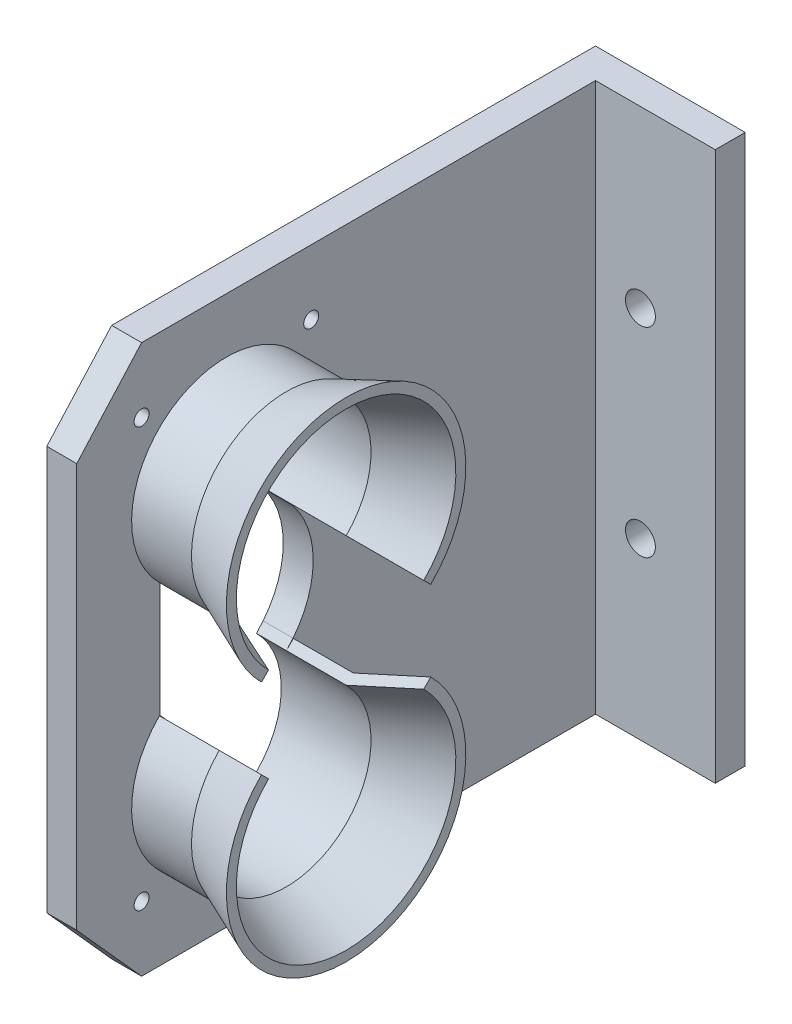
SolidWorks part; units mm, degrees
ref_plane "前视基准面" through (0, 0, 0) normal (0, 0, 1) x (1, 0, 0)
ref_plane "上视基准面" through (0, 0, 0) normal (0, 1, 0) x (1, 0, 0)
ref_plane "右视基准面" through (0, 0, 0) normal (1, 0, 0) x (0, 0, -1)
other "Configuration Table"
sketch "草图1" plane through (0, 0, 0) normal (0, 1, 0) x (1, 0, 0)
  line L7 (22.8824, -27.7157) -> (25.8824, -27.7157)
  line L8 (25.8824, -27.7157) -> (25.8824, 24.2843)
  line L9 (25.8824, 24.2843) -> (37.8824, 24.2843)
  line L10 (37.8824, 24.2843) -> (37.8824, 27.2843)
  line L11 (37.8824, 27.2843) -> (22.8824, 27.2843)
  line L12 (22.8824, 27.2843) -> (22.8824, -27.7157)
extrude "凸台-拉伸1" add sketch "草图1" along normal mid plane 55
ref_plane "基准面1" through (0, 0, -27.2843) normal (0, 0, -1) x (-1, 0, 0)
sketch "草图2" plane through (0, 0, -27.2843) normal (0, 0, -1) x (-1, 0, 0)
  line L3 (-25.8824, 27.5) -> (-25.8824, -27.5)
  line L4 (-24.3824, 27.5) -> (-24.3824, -27.5)
  line L5 (-25.8824, 27.5) -> (-10.8824, 27.5) construction
  line L6 (-25.8824, -27.5) -> (-10.8824, -27.5) construction
  line L7 (-22.8824, 27.5) -> (-22.8824, -27.5)
  circle A2 centre (-30.3824, -10) radius 1.5
  circle A3 centre (-30.3824, 10) radius 1.5
  dimension "D4" = 1.5
ref_plane "基准面2" through (25.8824, 0, 0) normal (1, 0, 0) x (0, 0, -1)
sketch "草图3" plane through (25.8824, 0, 0) normal (1, 0, 0) x (0, 0, -1)
  line L0 (-27.7157, 27.5) -> (-27.7157, -27.5) construction
  line L1 (-22.7157, 22.5) -> (-2.7157, 22.5)
  line L2 (-22.7157, 22.5) -> (-22.7157, -22.5)
  line L3 (-22.7157, -22.5) -> (-2.7157, -22.5)
  line L4 (-2.7157, 22.5) -> (-2.7157, -22.5)
  line L5 (-22.7157, 22.5) -> (-2.7157, -22.5) construction
  line L6 (-22.7157, -22.5) -> (-2.7157, 22.5) construction
  line L7 (-12.7157, 22.5) -> (-12.7157, 22)
  line L8 (-12.7157, 12.5) -> (-6.7053, 6.4896)
  line L9 (-12.7157, 12.5) -> (-18.7261, 6.4896)
  line L10 (-12.7157, -12.5) -> (-18.7261, -6.4896)
  line L11 (-12.7157, -12.5) -> (-6.7053, -6.4896)
  line L12 (-12.7157, -22) -> (-12.7157, -22.5)
  line L13 (-12.7157, -4) -> (-12.7157, -21)
  line L14 (-12.7157, 3) -> (-12.7157, -3)
  line L15 (-12.7157, 21) -> (-12.7157, 4)
  line L16 (-22.7157, 0) -> (-2.7157, 0)
  line L17 (-18.7261, 6.4896) -> (-19.3945, 5.744)
  line L18 (-6.7053, 6.4896) -> (-6.0369, 5.744)
  line L19 (-6.0369, -5.744) -> (-6.7053, -6.4896)
  line L20 (-19.3945, -5.744) -> (-18.7261, -6.4896)
  line L21 (-19.3945, 5.744) -> (-19.3945, -5.744)
  line L22 (-27.7157, 27.5) -> (-27.7157, 20.2498)
  line L23 (-27.7157, 20.2498) -> (-21.2157, 27.5)
  line L24 (-27.7157, 27.5) -> (27.2843, 27.5) construction
  line L25 (-21.2157, 27.5) -> (-27.7157, 27.5)
  line L26 (-27.7157, -20.2498) -> (-21.2157, -27.5)
  line L27 (-27.7157, -27.5) -> (-27.7157, -20.2498)
  line L28 (-21.2157, -27.5) -> (-27.7157, -27.5)
  circle A0 centre (-12.7157, 12.5) radius 8.5
  circle A1 centre (-12.7157, -12.5) radius 8.5
  arc A2 (-6.0369, 5.744) -> (-6.0369, -5.744) centre (-13.1949, 0) cw
  circle A4 centre (-12.7157, 12.5) radius 9.5
  circle A5 centre (-12.7157, -12.5) radius 9.5
  circle A6 centre (-4.2157, -21) radius 0.75
  circle A7 centre (-21.2157, -21) radius 0.75
  circle A8 centre (-4.2157, 21) radius 0.75
  circle A9 centre (-21.2157, 21) radius 0.75
  point P0 (0, 0)
  dimension "D6" = 17
  dimension "D7" = 17
  dimension "D8" = 19
  dimension "D9" = 19
  dimension "D11" = 1.5
  dimension "D1" = 45
  dimension "D2" = 20
  dimension "D3" = 5
  dimension "D4" = 10
  dimension "D5" = 10
  dimension "D10" = 1.5
  dimension "D12" = 1.5
  dimension "D13" = 6.5
extrude "切除-拉伸3" cut sketch "草图3" against normal blind 3
ref_plane "基准面4" through (0, 0, 12.7157) normal (0, 0, 1) x (0, -1, 0)
sketch "草图5" plane through (0, 0, 12.7157) normal (0, 0, 1) x (0, -1, 0)
  line L0 (-3, 25.8824) -> (-22, 25.8824) construction
  line L2 (-3, 25.8824) -> (-22, 25.8824)
  line L4 (-3, 25.8824) -> (-22, 25.8824)
  line L6 (-22, 25.8824) -> (-21, 25.8824)
  line L9 (-12.5, 32.8824) -> (-12.5, 25.8824)
  line L10 (-21, 25.8824) -> (-21, 31.8824)
  line L14 (-22, 31.8824) -> (-22, 25.8824)
  line L15 (-21, 31.8824) -> (-23.5, 37.8824)
  line L16 (-23.5, 37.8824) -> (-24.5, 37.8824)
  line L17 (-24.5, 37.8824) -> (-22, 31.8824)
  point P2 (-24, 37.8824)
  point P3 (0, 0)
  dimension "D1" = 6
  dimension "D2" = 6
revolve "旋转1" add sketch "草图5" angle 270 mid plane about L9
mirror "镜向1" about plane through (0, 0, 0) normal (0, 1, 0) of "旋转1"
extrude "切除-拉伸4" cut sketch "草图2" against normal blind 3 contours A3 | A2
